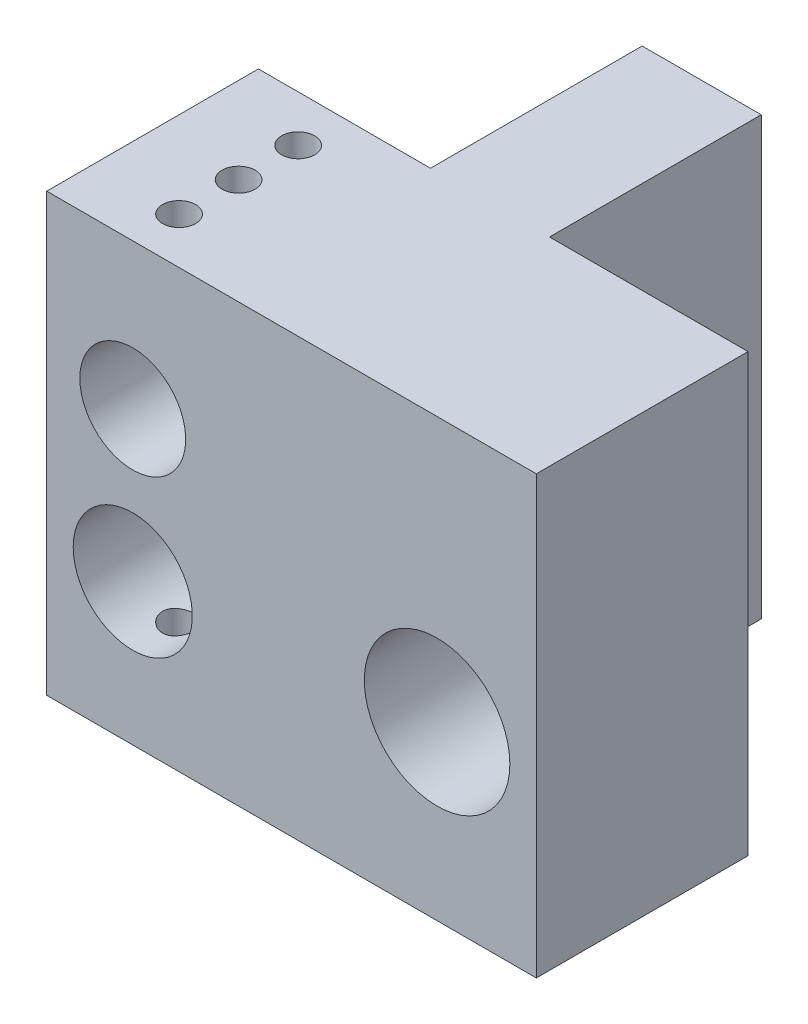
SolidWorks part; units mm, degrees
ref_plane "Plan de face" through (0, 0, 0) normal (0, 0, 1) x (1, 0, 0)
ref_plane "Plan de dessus" through (0, 0, 0) normal (0, 1, 0) x (1, 0, 0)
ref_plane "Plan de droite" through (0, 0, 0) normal (1, 0, 0) x (0, 0, -1)
sketch "Esquisse1" plane through (0, 0, 0) normal (0, 1, 0) x (1, 0, 0)
  line L1 (18.5, -8) -> (-18.5, -8)
  line L2 (18.5, -8) -> (18.5, 8)
  line L3 (18.5, 8) -> (-18.5, 8)
  line L4 (-18.5, -8) -> (-18.5, 8)
  line L5 (18.5, -8) -> (-18.5, 8) construction
  line L6 (18.5, 8) -> (-18.5, -8) construction
  point P0 (0, 0)
  dimension "D1" = 16
  dimension "D2" = 37
extrude "Boss.-Extru.1" add sketch "Esquisse1" along normal mid plane 33
sketch "Esquisse3" plane through (0, 0, 8) normal (0, 0, 1) x (1, 0, 0)
  line L0 (-18.5, -16.5) -> (18.5, -16.5) construction
  line L1 (18.5, 16.5) -> (18.5, -16.5) construction
  circle A0 centre (11, -3.5) radius 5.5
  dimension "D1" = 11
  dimension "D2" = 13
  dimension "D3" = 7.5
extrude "Enlèv. mat.-Extru.2" cut sketch "Esquisse3" against normal through all
sketch "Esquisse14" plane through (0, 0, -8) normal (0, 0, -1) x (-1, 0, 0)
  line L0 (-18.5, -16.5) -> (18.5, -16.5) construction
  line L1 (18.5, 16.5) -> (18.5, -16.5) construction
  circle A0 centre (12, -5.8) radius 4.5
  dimension "D1" = 9
  dimension "D2" = 10.7
  dimension "D3" = 6.5
extrude "Enlèv. mat.-Extru.3" cut sketch "Esquisse14" against normal through all
sketch "Esquisse15" plane through (0, 0, -8) normal (0, 0, -1) x (-1, 0, 0)
  line L0 (-18.5, -16.5) -> (18.5, -16.5) construction
  line L4 (18.5, 16.5) -> (18.5, -16.5) construction
  circle A0 centre (12, 5.5) radius 4
  dimension "D1" = 8
  dimension "D2" = 22
  dimension "D3" = 6.5
extrude "Enlèv. mat.-Extru.4" cut sketch "Esquisse15" against normal through all
hole_wizard "Trou taraudé M34" positions "Esquisse11" profile "Esquisse10" tap size "M3" standard "Iso"
sketch "Esquisse11" plane through (0, 16.5, 0) normal (0, 1, 0) x (1, 0, 0)
  line L0 (-12, -4.5) -> (-12, 4.5)
  line L14 (0, 0) -> (-12, 0) construction
  line L16 (-8, 8) -> (-16, 8) construction
  line L17 (-8, 8) -> (-16, 8)
  line L18 (-16, -8) -> (-8, -8) construction
  line L19 (-16, -8) -> (-8, -8)
  line L20 (-12, 8) -> (-12, 4.5) construction
  point P1 (-12, -4.5)
  point P2 (-12, 4.5)
  dimension "D1" = 3.5
cosmetic thread "Filetage de perçage11" parameters "D2"=3
cosmetic thread "Filetage de perçage12" parameters "D2"=3
sketch "Esquisse10" plane through (-12, 16.5, 4.5) normal (1, 0, 0) x (0, 0, 1)
  line L0 (0, 0) -> (0, 7)
  line L1 (0, 7) -> (1.25, 7)
  line L2 (1.25, 7) -> (1.25, 0)
  line L5 (1.25, 0) -> (0, 0)
  line L11 (0, -6.35) -> (0, 107.95) construction
  dimension "Diamètre du trou pour taraudage jusqu'au prochain" = 2.5
  dimension "Profondeur du trou pour taraudage jusqu'au prochain" = 7
hole_wizard "Trou taraudé M35" positions "Esquisse13" profile "Esquisse12" tap size "M3" standard "Iso"
sketch "Esquisse13" plane through (0, -16.5, 0) normal (0, -1, 0) x (-1, 0, 0)
  point P0 (12, -4.5)
  point P3 (12, 4.5)
cosmetic thread "Filetage de perçage9" parameters "D2"=3
cosmetic thread "Filetage de perçage10" parameters "D2"=3
sketch "Esquisse12" plane through (-12, -16.5, 4.5) normal (1, 0, 0) x (0, 0, -1)
  line L0 (0, 0) -> (0, 6.2)
  line L1 (0, 6.2) -> (1.25, 6.2)
  line L2 (1.25, 6.2) -> (1.25, 0)
  line L5 (1.25, 0) -> (0, 0)
  line L11 (0, -6.35) -> (0, 107.95) construction
  dimension "Diamètre du trou pour taraudage jusqu'au prochain" = 2.5
  dimension "Profondeur du trou pour taraudage jusqu'au prochain" = 6.2
hole_wizard "Trou taraudé M36" positions "Esquisse17" profile "Esquisse16" tap size "M3" standard "Iso"
sketch "Esquisse17" plane through (-1.446, 16.5, -0.3035) normal (0, -1, 0) x (-1, 0, 0)
  line L0 (6.554, -0.3035) -> (14.554, -0.3035)
  line L1 (6.554, 7.6965) -> (6.554, -8.3035) construction
  line L2 (14.554, -8.3035) -> (14.554, 7.6965) construction
  line L3 (14.554, -8.3035) -> (14.554, 7.6965)
  line L4 (6.554, 7.6965) -> (6.554, -8.3035)
  point P9 (10.554, -0.3035)
sketch "Esquisse16" plane through (-12, 16.5, 0) normal (1, 0, 0) x (0, 0, 1)
  line L0 (0, 0) -> (0, 7)
  line L1 (0, 7) -> (1.25, 7)
  line L2 (1.25, 7) -> (1.25, 0)
  line L5 (1.25, 0) -> (0, 0)
  line L11 (0, -6.35) -> (0, 107.95) construction
  dimension "Diamètre du trou pour taraudage jusqu'au prochain" = 2.5
  dimension "Profondeur du trou pour taraudage jusqu'au prochain" = 7
cosmetic thread "Filetage de perçage13" parameters "D2"=3
sketch "Esquisse18" plane through (0, -16.5, 0) normal (0, -1, 0) x (1, 0, 0)
  line L1 (-5.5, -8) -> (3.5, -8)
  line L2 (-5.5, -8) -> (-5.5, -24)
  line L3 (-5.5, -24) -> (3.5, -24)
  line L4 (3.5, -8) -> (3.5, -24)
  line L5 (18.5, 8) -> (18.5, -8) construction
  line L6 (-18.5, -8) -> (-18.5, 8) construction
  line L7 (18.5, -8) -> (-18.5, -8) construction
  dimension "D1" = 15
  dimension "D2" = 13
  dimension "D3" = 16
extrude "Boss.-Extru.2" add sketch "Esquisse18" against normal up to surface (33 mm away) up to face at (-12, 16.5, 1.25)
sketch "Esquisse20" plane through (-5.5, 0, 0) normal (-1, 0, 0) x (0, 0, 1)
  line L0 (8, 16.5) -> (8, -16.5) construction
  line L1 (-8, -16.5) -> (-24, -16.5) construction
  circle A0 centre (-17.1, -3.55) radius 4.5
  dimension "D3" = 9
  dimension "D1" = 25.1
  dimension "D2" = 12.95
extrude "Enlèv. mat.-Extru.5" cut sketch "Esquisse20" against normal through all
